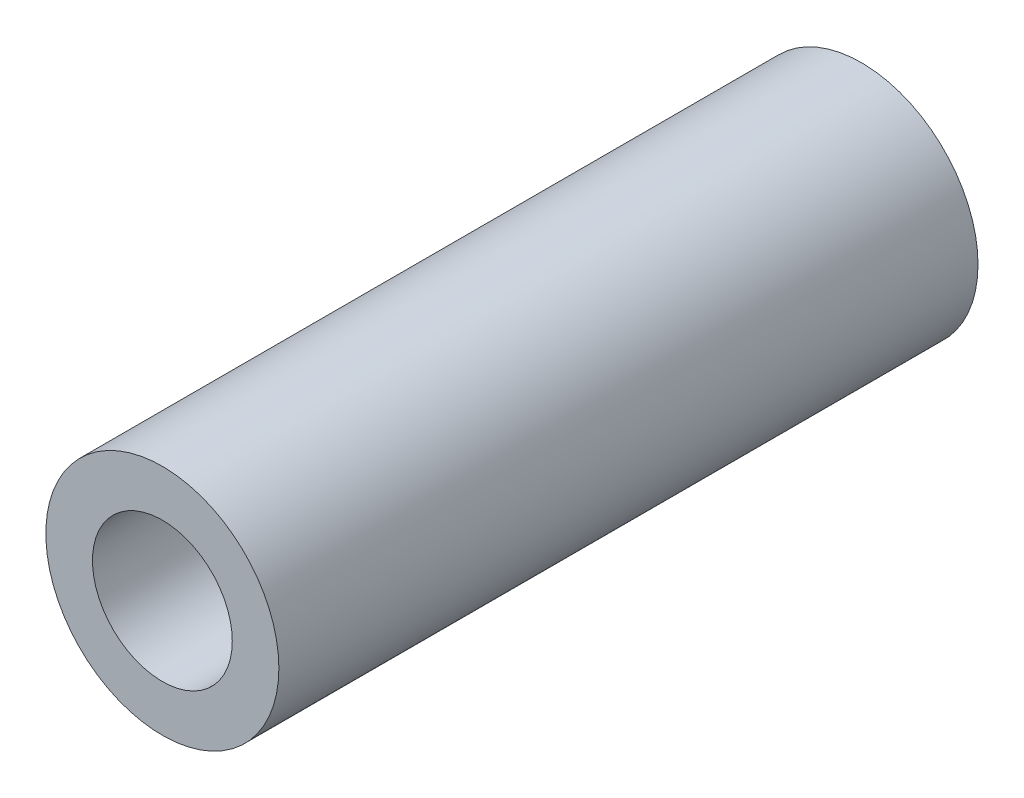
SolidWorks part; units mm, degrees
ref_plane "Alzado" through (0, 0, 0) normal (0, 0, 1) x (1, 0, 0)
ref_plane "Planta" through (0, 0, 0) normal (0, 1, 0) x (1, 0, 0)
ref_plane "Vista lateral" through (0, 0, 0) normal (1, 0, 0) x (0, 0, -1)
sketch "Croquis1" plane through (0, 0, 0) normal (0, 0, 1) x (1, 0, 0)
  circle A0 centre (0, 0) radius 1.5
  circle A1 centre (0, 0) radius 2.5
extrude "Saliente-Extruir1" add sketch "Croquis1" along normal blind 15
